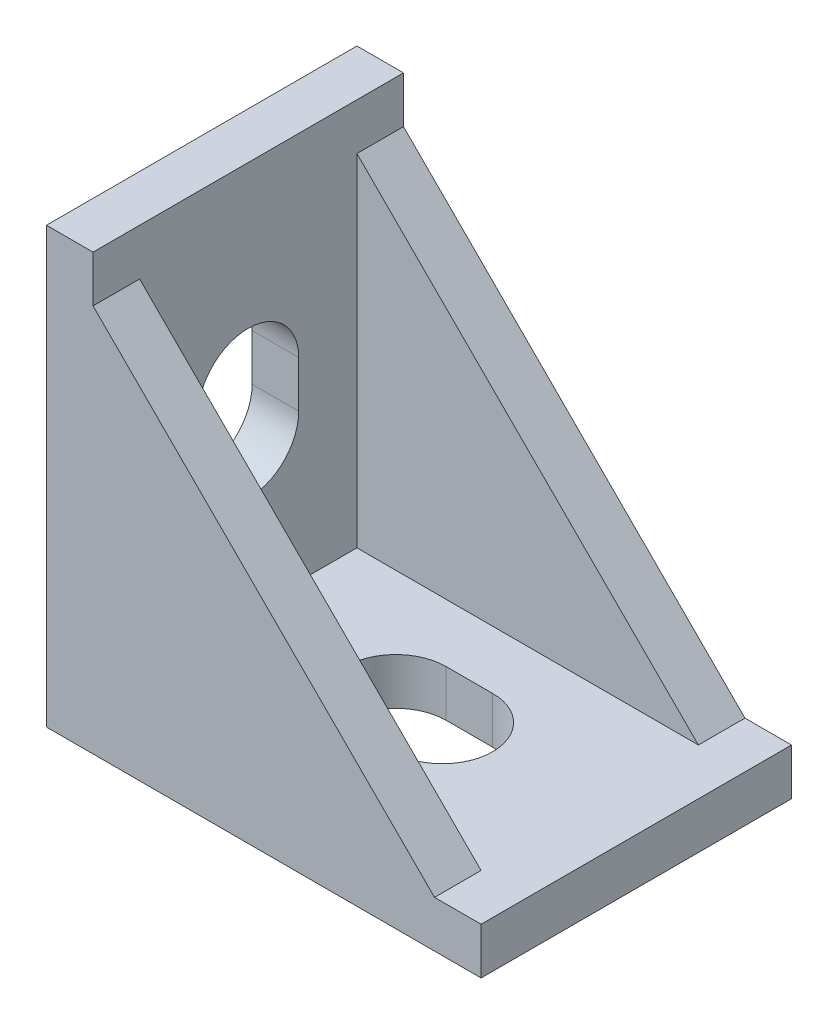
SolidWorks part; units mm, degrees
ref_plane "Front Plane" through (0, 0, 0) normal (0, 0, 1) x (1, 0, 0)
ref_plane "Top Plane" through (0, 0, 0) normal (0, 1, 0) x (1, 0, 0)
ref_plane "Right Plane" through (0, 0, 0) normal (1, 0, 0) x (0, 0, -1)
sketch "Sketch1" plane through (0, 0, 0) normal (0, 0, 1) x (1, 0, 0)
  line L0 (0, 0) -> (0, 28)
  line L1 (0, 28) -> (3, 28)
  line L2 (3, 28) -> (3, 25)
  line L3 (28, 3) -> (25, 3)
  line L4 (0, 0) -> (15.9837, 15.9837) construction
  line L5 (28, 0) -> (28, 3)
  line L6 (0, 0) -> (28, 0)
  line L7 (25, 3) -> (3, 25)
  dimension "D1" = 28
  dimension "D2" = 3
  dimension "D3" = 3
  dimension "D4" = 45
extrude "Boss-Extrude1" add sketch "Sketch1" along normal blind 20
sketch "Sketch2" plane through (0, 3, 0) normal (0, 1, 0) x (1, 0, 0)
  line L0 (25, -17) -> (3, -17)
  line L1 (25, -20) -> (25, 0) construction
  line L2 (3, -17) -> (3, -3)
  line L3 (3, -3) -> (25, -3)
  line L4 (25, -17) -> (25, -3)
  line L5 (28, -20) -> (25, -20) construction
  line L6 (28, 0) -> (25, 0) construction
  dimension "D1" = 3
  dimension "D2" = 3
  dimension "D3" = 22
extrude "Cut-Extrude1" cut sketch "Sketch2" along normal through all
sketch "Sketch3" plane through (0, 0, 0) normal (0, -1, 0) x (1, 0, 0)
  line L0 (28, 20) -> (0, 0)
  line L1 (14, 10) -> (15.5, 10)
  line L2 (14, 10) -> (14, -2.0596) construction
  line L3 (15.5, 6.75) -> (12.5, 6.75)
  line L4 (12.5, 13.25) -> (15.5, 13.25)
  arc A0 (12.4455, 8.8897) -> (12.25, 10) centre (15.5, 10) ccw
  arc A1 (12.5, 6.75) -> (12.5, 13.25) centre (12.5, 10) cw
  arc A2 (15.5, 6.75) -> (15.5, 13.25) centre (15.5, 10) ccw
  dimension "D1" = 3.25
  dimension "D2" = 3
extrude "Cut-Extrude2" cut sketch "Sketch3" against normal through all
ref_plane "Plane1" through (0, 0, 0) normal (-0.7071, 0.7071, 0) x (0, 0, 1)
mirror "Mirror1" about plane through (0, 0, 0) normal (-0.7071, 0.7071, 0) of "Cut-Extrude2"
